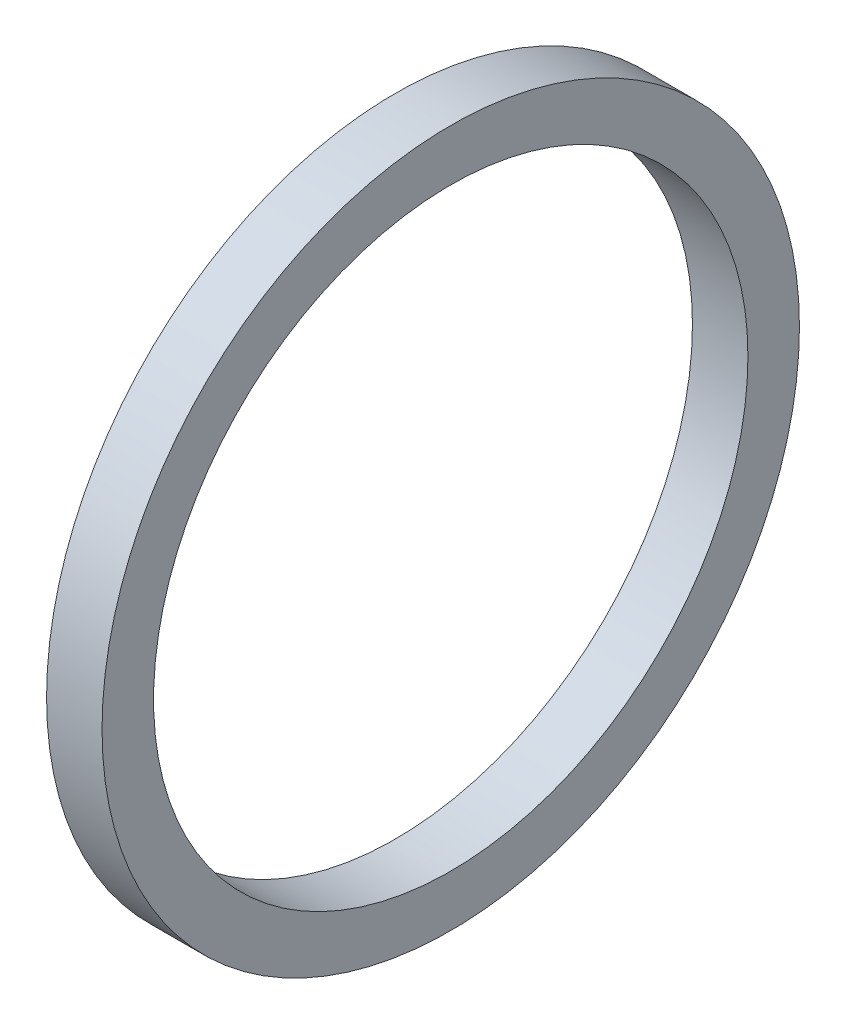
SolidWorks part; units mm, degrees
material "Silicon Rubber"
ref_plane "Front Plane" through (0, 0, 0) normal (0, 0, 1) x (1, 0, 0)
ref_plane "Top Plane" through (0, 0, 0) normal (0, 1, 0) x (1, 0, 0)
ref_plane "Right Plane" through (0, 0, 0) normal (1, 0, 0) x (0, 0, -1)
sketch "Sketch1" plane through (0, 0, 0) normal (1, 0, 0) x (0, 0, -1)
  circle A0 centre (0, 0) radius 44
  circle A1 centre (0, 0) radius 37.5
  dimension "D1" = 88
  dimension "D2" = 75
extrude "Boss-Extrude1" add sketch "Sketch1" along normal blind 7
